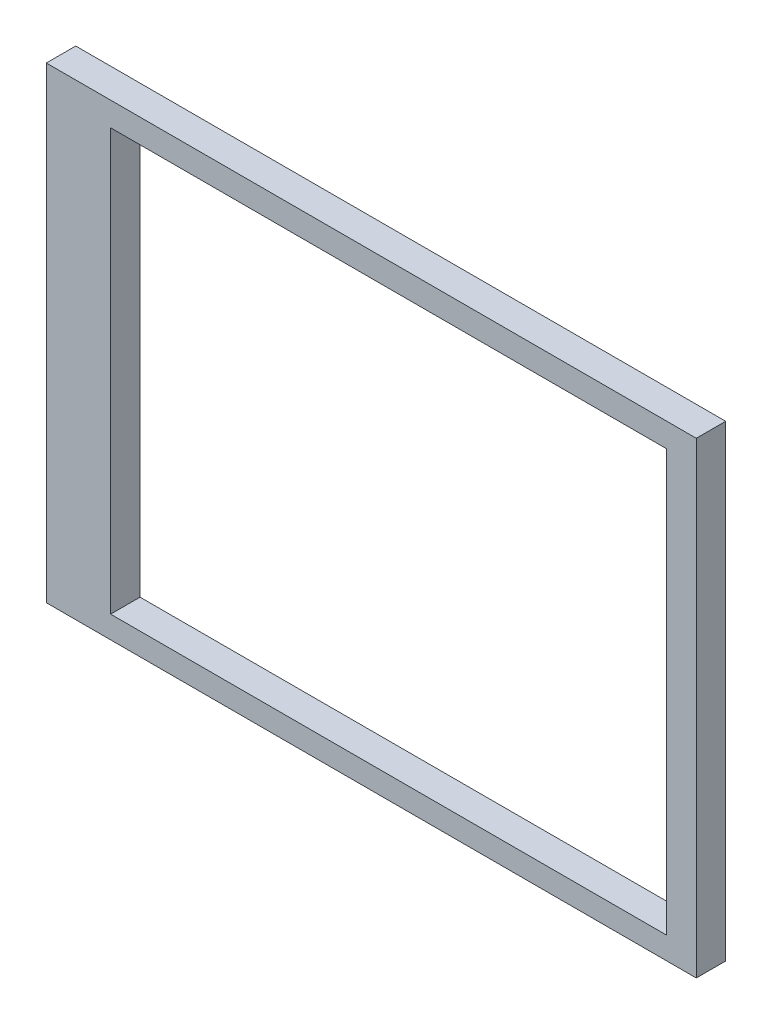
SolidWorks part; units mm, degrees
ref_plane "Front Plane" through (0, 0, 0) normal (0, 0, 1) x (1, 0, 0)
ref_plane "Top Plane" through (0, 0, 0) normal (0, 1, 0) x (1, 0, 0)
ref_plane "Right Plane" through (0, 0, 0) normal (1, 0, 0) x (0, 0, -1)
sketch "Sketch1" plane through (0, 0, 0) normal (0, 0, 1) x (1, 0, 0)
  line L0 (0, 20.04) -> (0, -20.04) construction
  line L1 (-32.56, -22.16) -> (29.29, -22.16)
  line L2 (-32.56, -22.16) -> (-32.56, 22.32)
  line L3 (-32.56, 22.32) -> (29.29, 22.32)
  line L4 (29.29, -22.16) -> (29.29, 22.32)
  line L5 (-26.44, 20.04) -> (26.44, 20.04)
  line L6 (-26.44, 20.04) -> (-26.44, -20.04)
  line L7 (-26.44, -20.04) -> (26.44, -20.04)
  line L8 (26.44, 20.04) -> (26.44, -20.04)
  dimension "D1" = 44.48
  dimension "D2" = 61.85
  dimension "D3" = 6.12
  dimension "D4" = 2.12
  dimension "D5" = 2.85
  dimension "D6" = 2.28
extrude "Boss-Extrude1" add sketch "Sketch1" along normal blind 2.8
